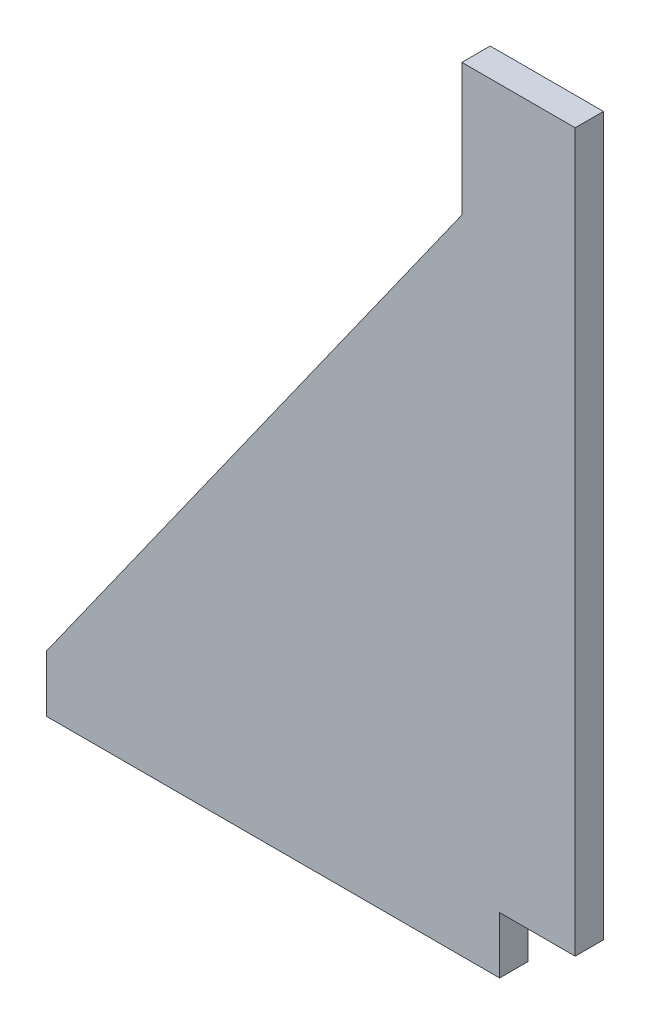
SolidWorks part; units mm, degrees
material "Pine"
ref_plane "Front Plane" through (0, 0, 0) normal (0, 0, 1) x (1, 0, 0)
ref_plane "Top Plane" through (0, 0, 0) normal (0, 1, 0) x (1, 0, 0)
ref_plane "Right Plane" through (0, 0, 0) normal (1, 0, 0) x (0, 0, -1)
sketch "Sketch1" plane through (0, 0, 0) normal (0, 0, 1) x (1, 0, 0)
  line L0 (0, 0) -> (304.8, 0)
  line L1 (304.8, 0) -> (304.8, 38.1)
  line L2 (304.8, 38.1) -> (355.6, 38.1)
  line L3 (355.6, 38.1) -> (355.6, 520.7)
  line L4 (355.6, 520.7) -> (279.4, 520.7)
  line L6 (0, 38.1) -> (0, 0)
  line L7 (0, 38.1) -> (279.4, 431.8)
  line L8 (279.4, 431.8) -> (279.4, 520.7)
  dimension "D1" = 304.8
  dimension "D2" = 50.8
  dimension "D3" = 38.1
  dimension "D4" = 482.6
  dimension "D5" = 76.2
  dimension "D6" = 88.9
extrude "Boss-Extrude1" add sketch "Sketch1" along normal mid plane 19.05 contours L6 L0 L1 L2 L3 L4 L8 L7
